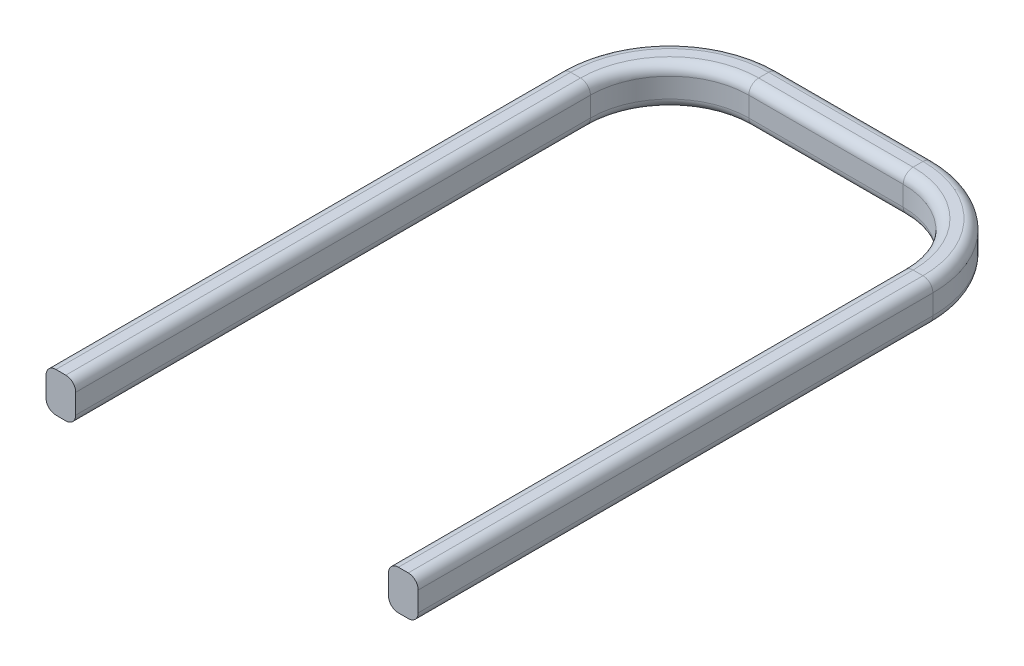
SolidWorks part; units mm, degrees
ref_plane "Front Plane" through (0, 0, 0) normal (0, 0, 1) x (1, 0, 0)
ref_plane "Top Plane" through (0, 0, 0) normal (0, 1, 0) x (1, 0, 0)
ref_plane "Right Plane" through (0, 0, 0) normal (1, 0, 0) x (0, 0, -1)
sketch "Sketch2" plane through (0, 0, 0) normal (0, 1, 0) x (1, 0, 0)
  line L0 (-3.95, 0) -> (-3.95, 13)
  line L1 (-1.95, 15) -> (1.95, 15)
  line L2 (3.95, 13) -> (3.95, 0)
  arc A0 (-1.95, 15) -> (-3.95, 13) centre (-1.95, 13) ccw
  arc A1 (3.95, 13) -> (1.95, 15) centre (1.95, 13) ccw
  point P2 (0, 15)
  point P11 (-3.95, 15)
  dimension "D3" = 2
  dimension "D1" = 3.95
  dimension "D2" = 15
sketch "Sketch3" plane through (0, 0, 0) normal (0, 0, 1) x (1, 0, 0)
  line L1 (-3.95, 0) -> (-4.7, 0)
  line L2 (-3.95, 0) -> (-3.95, 1)
  line L3 (-3.95, 1) -> (-4.7, 1)
  line L4 (-4.7, 0) -> (-4.7, 1)
  dimension "D1" = 1
  dimension "D2" = 0.75
sweep "Sweep1" add profiles "Sketch3" path "Sketch2"
fillet "Fillet1" radius 0.25 20 edges at (4.7, 0, -6.5) (3.8945, 0, -14.9445) (0, 0, -15.75) (-3.8945, 0, -14.9445) (3.95, 0, -6.5) (3.3642, 0, -14.4142) (0, 0, -15) (-3.3642, 0, -14.4142) (3.95, 1, -6.5) (3.3642, 1, -14.4142) (0, 1, -15) (-3.3642, 1, -14.4142) (4.7, 1, -6.5) (3.8945, 1, -14.9445) (0, 1, -15.75) (-3.8945, 1, -14.9445) (-4.7, 0, -6.5) (-3.95, 0, -6.5) (-3.95, 1, -6.5) (-4.7, 1, -6.5)
scale "Scale1" scale about centroid uniform scaling yes scale factor 0.445
